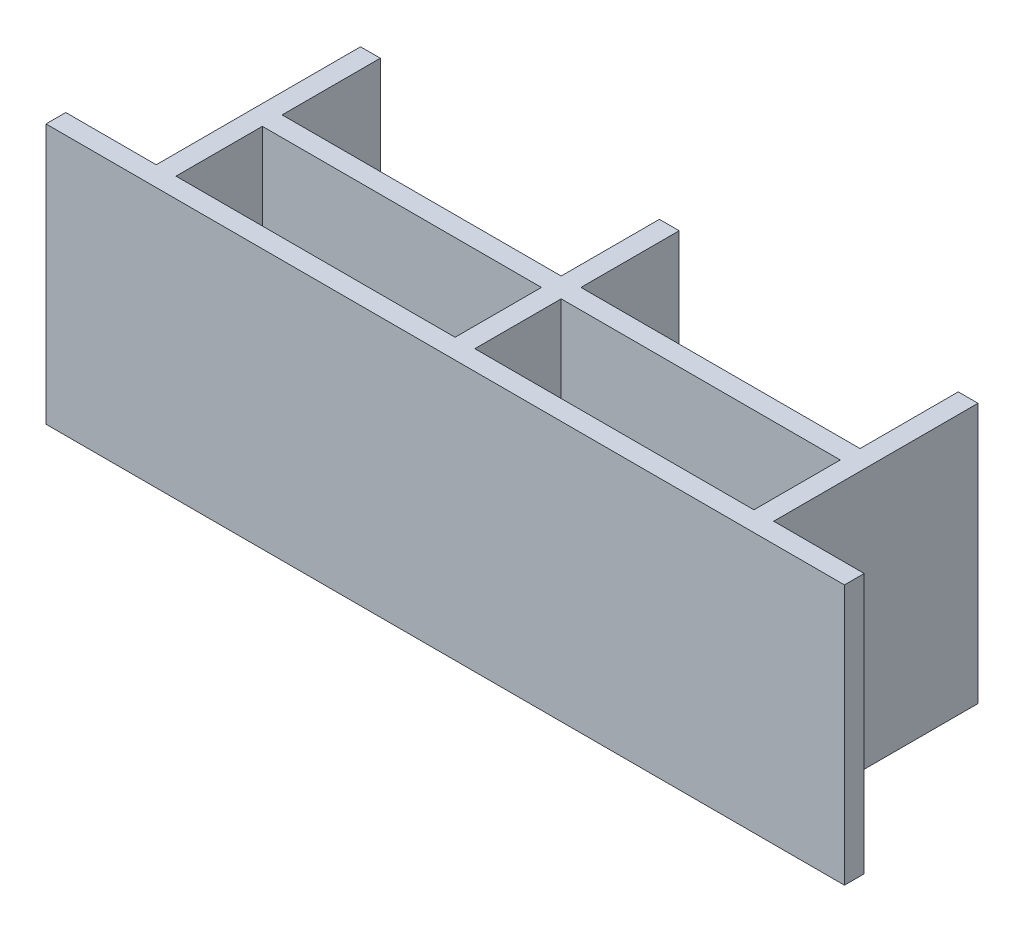
SolidWorks part; units mm, degrees
ref_plane "Front Plane" through (0, 0, 0) normal (0, 0, 1) x (1, 0, 0)
ref_plane "Top Plane" through (0, 0, 0) normal (0, 1, 0) x (1, 0, 0)
ref_plane "Right Plane" through (0, 0, 0) normal (1, 0, 0) x (0, 0, -1)
sketch "Sketch1" plane through (0, 0, 0) normal (0, 1, 0) x (1, 0, 0)
  line L1 (0, 0) -> (101, 0)
  line L2 (0, 0) -> (0, 43)
  line L3 (0, 43) -> (101, 43)
  line L4 (101, 0) -> (101, 43)
  dimension "D1" = 43
  dimension "D2" = 101
extrude "Boss-Extrude1" add sketch "Sketch1" along normal blind 32.9
sketch "Sketch4" plane through (0, 32.9, 0) normal (0, 1, 0) x (1, 0, 0)
  line L0 (0, 43) -> (0, 0) construction
  line L1 (0, 14.656) -> (101, 14.656)
  line L2 (0, 14.656) -> (0, 0)
  line L3 (0, 0) -> (101, 0)
  line L4 (101, 14.656) -> (101, 0)
  line L5 (101, 43) -> (0, 43) construction
  line L6 (101, 43) -> (89.549, 43)
  line L7 (101, 43) -> (101, 17.156)
  line L8 (101, 17.156) -> (89.549, 17.156)
  line L9 (89.549, 43) -> (89.549, 17.156)
  line L10 (0, 43) -> (11.445, 43)
  line L11 (0, 43) -> (0, 17.156)
  line L12 (0, 17.156) -> (11.445, 17.156)
  line L13 (11.445, 43) -> (11.445, 17.156)
  line L14 (13.945, 43) -> (49.247, 43)
  line L15 (13.945, 43) -> (13.945, 30.578)
  line L16 (13.945, 30.578) -> (49.247, 30.578)
  line L17 (49.247, 43) -> (49.247, 30.578)
  line L19 (51.747, 43) -> (87.049, 43)
  line L20 (51.747, 43) -> (51.747, 30.578)
  line L21 (51.747, 30.578) -> (87.049, 30.578)
  line L22 (87.049, 43) -> (87.049, 30.578)
  line L23 (51.747, 28.078) -> (87.049, 28.078)
  line L24 (51.747, 28.078) -> (51.747, 17.156)
  line L25 (51.747, 17.156) -> (87.049, 17.156)
  line L26 (87.049, 28.078) -> (87.049, 17.156)
  line L27 (49.247, 28.078) -> (13.945, 28.078)
  line L28 (49.247, 28.078) -> (49.247, 17.156)
  line L29 (49.247, 17.156) -> (13.945, 17.156)
  line L30 (13.945, 28.078) -> (13.945, 17.156)
  dimension "D1" = 2.5
  dimension "D2" = 2.5
  dimension "D3" = 2.5
  dimension "D4" = 2.5
  dimension "D5" = 2.5
  dimension "D6" = 2.5
  dimension "D7" = 2.5
  dimension "D8" = 2.5
  dimension "D9" = 2.5
  dimension "D10" = 2.5
  dimension "D11" = 2.5
  dimension "D12" = 2.5
  dimension "D13" = 10.922
  dimension "D14" = 10.922
  dimension "D15" = 12.422
  dimension "D16" = 12.422
  dimension "D17" = 35.302
  dimension "D18" = 35.302
  dimension "D19" = 35.302
  dimension "D20" = 35.302
  dimension "D21" = 11.445
  dimension "D22" = 11.451
extrude "Cut-Extrude2" cut sketch "Sketch4" against normal blind 32.9
